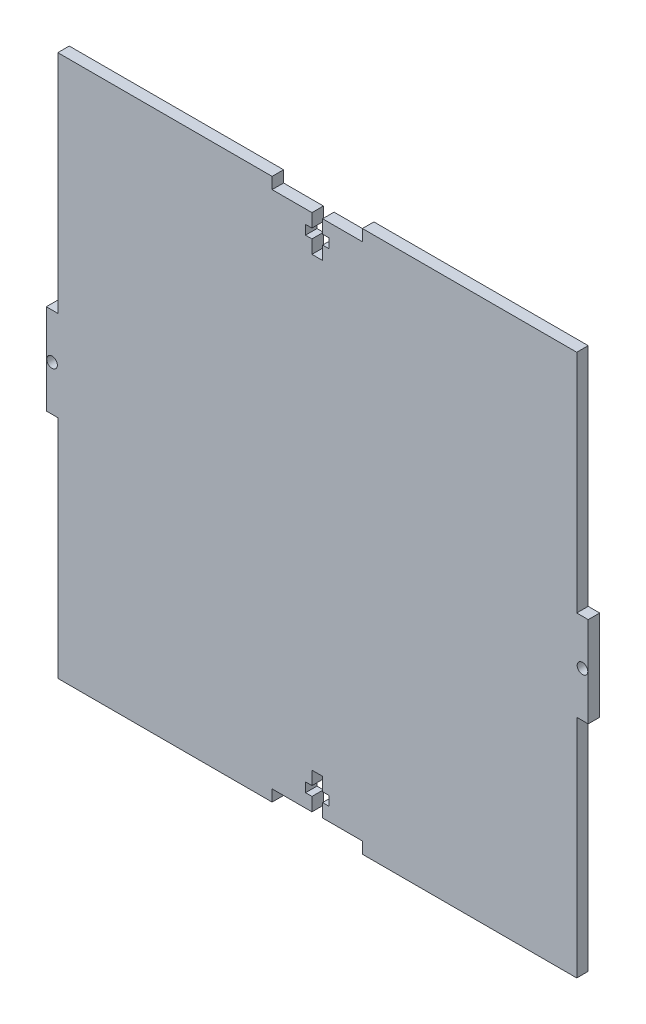
SolidWorks part; units mm, degrees
ref_plane "Front Plane" through (0, 0, 0) normal (0, 0, 1) x (1, 0, 0)
ref_plane "Top Plane" through (0, 0, 0) normal (0, 1, 0) x (1, 0, 0)
ref_plane "Right Plane" through (0, 0, 0) normal (1, 0, 0) x (0, 0, -1)
sketch "Sketch1" plane through (0, 0, 0) normal (0, 0, 1) x (1, 0, 0)
  line L0 (0, 75) -> (0, -75) construction
  line L1 (-71.825, 75) -> (71.825, 75)
  line L2 (-71.825, 75) -> (-71.825, -75)
  line L3 (-71.825, -75) -> (71.825, -75)
  line L4 (71.825, 75) -> (71.825, -75)
  line L5 (-71.825, 75) -> (71.825, -75) construction
  line L6 (-71.825, -75) -> (71.825, 75) construction
  line L7 (-71.825, 0) -> (71.825, 0) construction
  line L8 (-3.25, -65.525) -> (3.25, -65.525)
  line L9 (12.5, 75) -> (-12.5, 75)
  line L10 (12.5, 75) -> (12.5, 71.825)
  line L11 (12.5, 71.825) -> (-12.5, 71.825)
  line L12 (-12.5, 75) -> (-12.5, 71.825)
  line L13 (12.5, 75) -> (-12.5, 71.825) construction
  line L14 (12.5, 71.825) -> (-12.5, 75) construction
  line L15 (-1.47, 71.825) -> (1.47, 71.825)
  line L16 (-1.47, 71.825) -> (-1.47, 61.825)
  line L17 (-1.47, 61.825) -> (1.47, 61.825)
  line L18 (1.47, 71.825) -> (1.47, 61.825)
  line L19 (-1.47, 71.825) -> (1.47, 61.825) construction
  line L20 (-1.47, 61.825) -> (1.47, 71.825) construction
  line L21 (-3.25, 68.125) -> (3.25, 68.125)
  line L22 (-3.25, 68.125) -> (-3.25, 65.525)
  line L23 (-3.25, 65.525) -> (3.25, 65.525)
  line L24 (3.25, 68.125) -> (3.25, 65.525)
  line L25 (-3.25, 68.125) -> (3.25, 65.525) construction
  line L26 (-3.25, 65.525) -> (3.25, 68.125) construction
  line L27 (3.25, -68.125) -> (3.25, -65.525)
  line L28 (-3.25, -68.125) -> (3.25, -68.125)
  line L29 (-3.25, -68.125) -> (-3.25, -65.525)
  line L30 (-1.47, -61.825) -> (1.47, -61.825)
  line L31 (1.47, -71.825) -> (1.47, -61.825)
  line L32 (-1.47, -71.825) -> (1.47, -71.825)
  line L33 (-1.47, -71.825) -> (-1.47, -61.825)
  line L34 (12.5, -71.825) -> (-12.5, -71.825)
  line L35 (-12.5, -75) -> (-12.5, -71.825)
  line L36 (12.5, -75) -> (-12.5, -75)
  line L37 (12.5, -75) -> (12.5, -71.825)
  line L38 (75, -12.5) -> (71.825, -12.5)
  line L39 (-75, 12.5) -> (-71.825, 12.5)
  line L40 (-75, 12.5) -> (-75, -12.5)
  line L41 (-75, -12.5) -> (-71.825, -12.5)
  line L42 (-71.825, 12.5) -> (-71.825, -12.5)
  line L43 (-75, 12.5) -> (-71.825, -12.5) construction
  line L44 (-75, -12.5) -> (-71.825, 12.5) construction
  line L45 (71.825, 12.5) -> (71.825, -12.5)
  line L46 (75, 12.5) -> (71.825, 12.5)
  line L47 (75, 12.5) -> (75, -12.5)
  circle A0 centre (-73.4125, 0) radius 1.47
  circle A1 centre (73.4125, 0) radius 1.47
  point P0 (0, 0)
  point P10 (0, 73.4125)
  point P15 (0, 66.825)
  point P20 (0, 66.825)
  point P37 (-73.4125, 0)
  dimension "D11" = 2.94
  dimension "D1" = 150
  dimension "D2" = 150
  dimension "D3" = 3.175
  dimension "D4" = 10
  dimension "D5" = 2.94
  dimension "D6" = 25
  dimension "D7" = 6.5
  dimension "D8" = 2.6
  dimension "D9" = 6.3
  dimension "D10" = 3.175
extrude "Boss-Extrude1" add sketch "Sketch1" along normal mid plane 3.175 contours L21 L24 L23 L18 L17 L16 L22 L11 L12 L1 L2 L3 L4 L10 | L40 L39 L42 L41 | A0 | L38 L45 L46 L47 | A1
